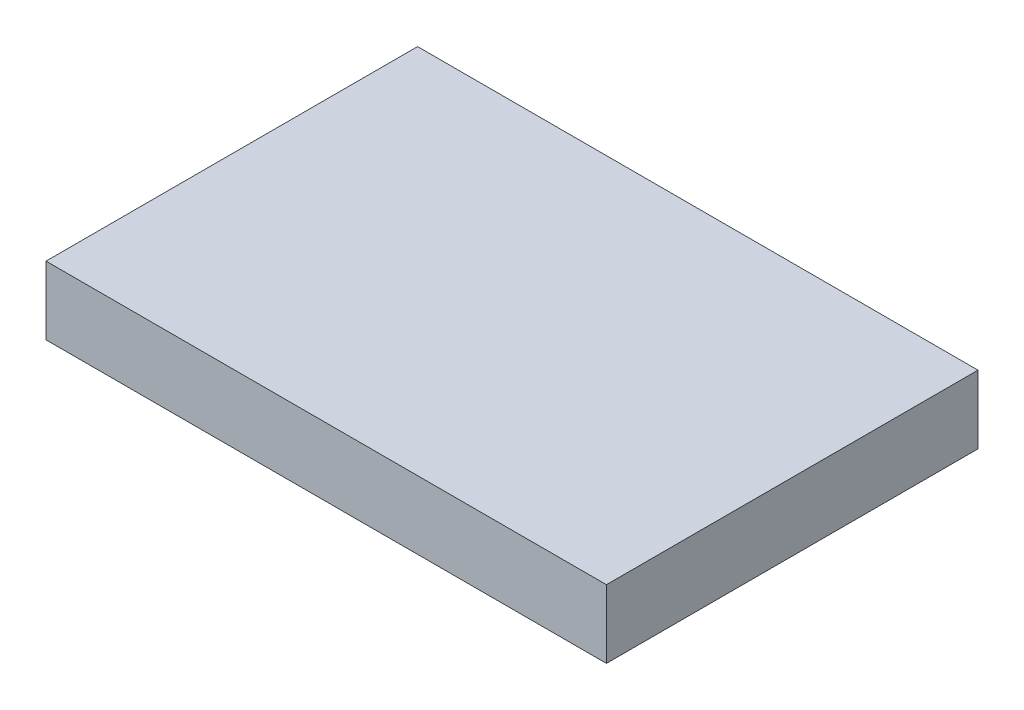
SolidWorks part; units mm, degrees
ref_plane "Front Plane" through (0, 0, 0) normal (0, 0, 1) x (1, 0, 0)
ref_plane "Top Plane" through (0, 0, 0) normal (0, 1, 0) x (1, 0, 0)
ref_plane "Right Plane" through (0, 0, 0) normal (1, 0, 0) x (0, 0, -1)
sketch "Sketch1" plane through (0, 0, 0) normal (0, 1, 0) x (1, 0, 0)
  line L1 (-41.1, 27.25) -> (41.1, 27.25)
  line L2 (-41.1, 27.25) -> (-41.1, -27.25)
  line L3 (-41.1, -27.25) -> (41.1, -27.25)
  line L4 (41.1, 27.25) -> (41.1, -27.25)
  point P4 (0, 27.25)
  point P6 (-41.1, 0)
  dimension "D1" = 54.5
  dimension "D2" = 82.2
extrude "Boss-Extrude1" add sketch "Sketch1" along normal blind 10
